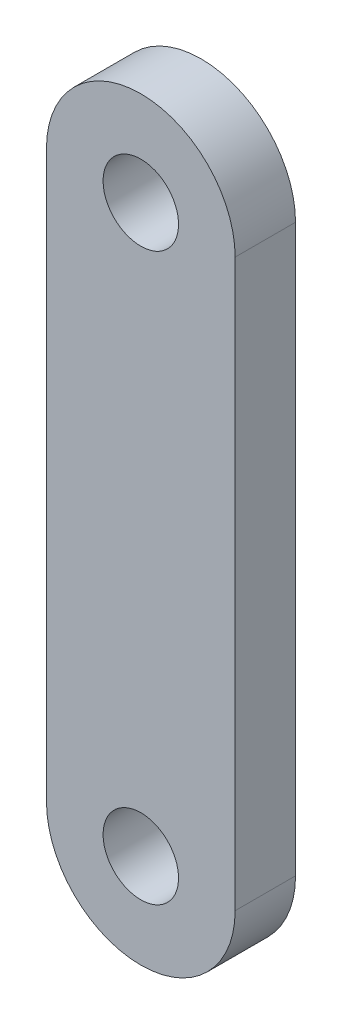
SolidWorks part; units mm, degrees
material "6061-T6 (SS)"
ref_plane "Front Plane" through (0, 0, 0) normal (1, 0, 0) x (0, 1, 0)
ref_plane "Top Plane" through (0, 0, 0) normal (0, 0, 1) x (0, 1, 0)
ref_plane "Right Plane" through (0, 0, 0) normal (0, 1, 0) x (-1, 0, 0)
sketch "Sketch1" plane through (0, 0, 0) normal (0, 0, 1) x (0, 1, 0)
  line L0 (-37.5, 0) -> (37.5, 0) construction
  line L1 (-37.5, 12.5) -> (37.5, 12.5)
  line L2 (-37.5, -12.5) -> (37.5, -12.5)
  arc A0 (-37.5, 12.5) -> (-37.5, -12.5) centre (-37.5, 0) ccw
  arc A1 (37.5, -12.5) -> (37.5, 12.5) centre (37.5, 0) ccw
  circle A2 centre (-37.5, 0) radius 5
  circle A3 centre (37.5, 0) radius 5
  point P2 (0, 0)
  dimension "D3" = 10
  dimension "D1" = 75
  dimension "D2" = 25
extrude "Boss-Extrude1" add sketch "Sketch1" along normal blind 8 contours L2 A1 L1 A0
sketch "Sketch2" plane through (0, 0, 0) normal (0, 0, -1) x (1, 0, 0)
  line L0 (0, 37.5) -> (0, -37.5) construction
  circle A0 centre (0, 37.5) radius 5
  circle A1 centre (0, -37.5) radius 5
  dimension "D2" = 10
  dimension "D1" = 75
extrude "Cut-Extrude1" cut sketch "Sketch2" against normal blind 8
